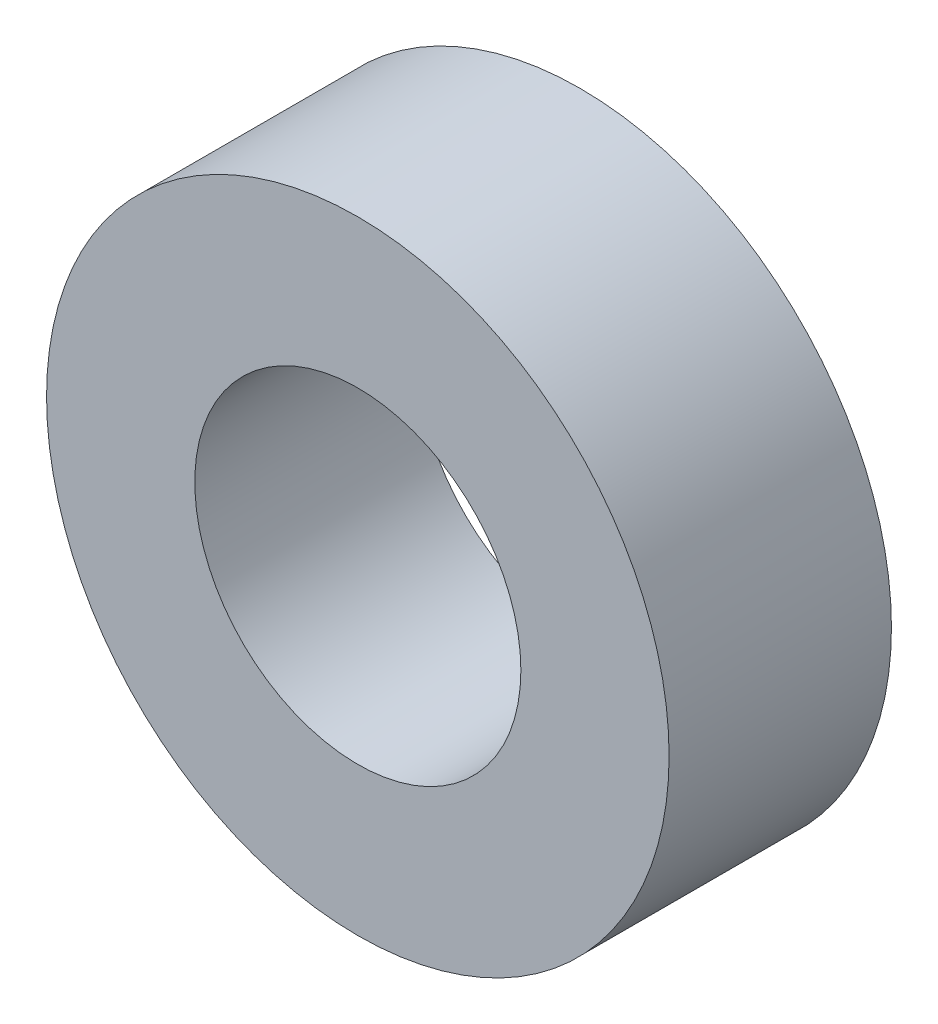
SolidWorks part; units mm, degrees
ref_plane "Front Plane" through (0, 0, 0) normal (0, 0, 1) x (1, 0, 0)
ref_plane "Top Plane" through (0, 0, 0) normal (0, 1, 0) x (1, 0, 0)
ref_plane "Right Plane" through (0, 0, 0) normal (1, 0, 0) x (0, 0, -1)
sketch "Sketch1" plane through (0, 0, 0) normal (0, 0, 1) x (1, 0, 0)
  circle A0 centre (0, 0) radius 2.1
  circle A1 centre (0, 0) radius 1.1
  dimension "D1" = 4.2
  dimension "D2" = 2.2
extrude "Boss-Extrude1" add sketch "Sketch1" along normal blind 1.5
